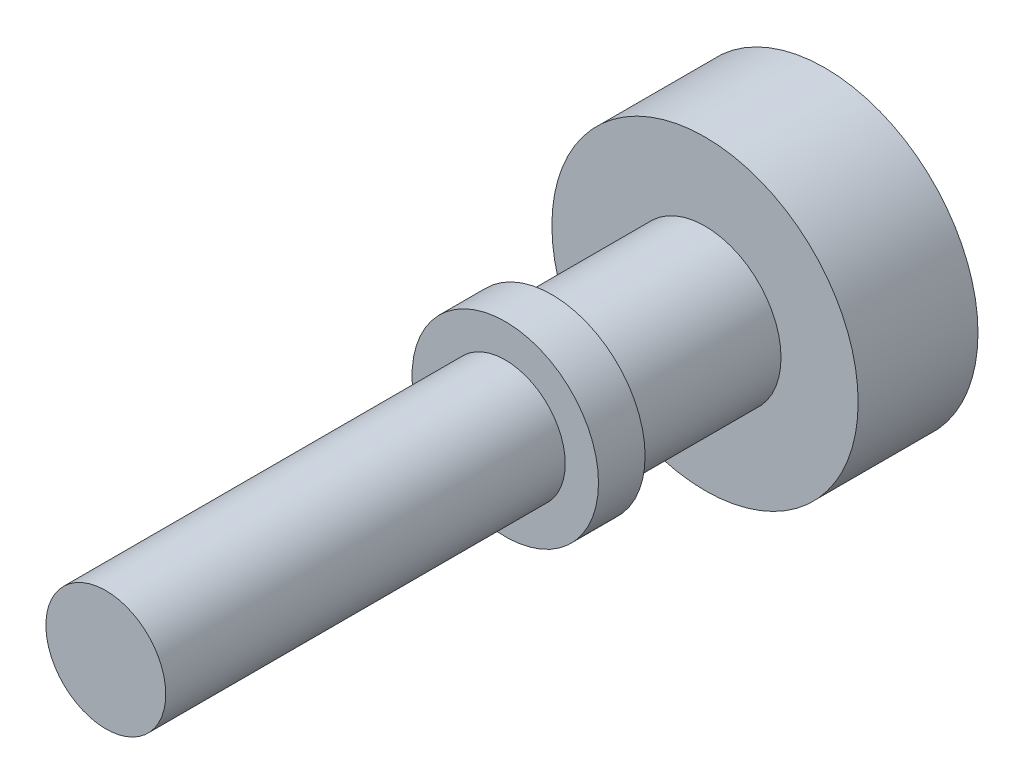
SolidWorks part; units mm, degrees
ref_plane "Front Plane" through (0, 0, 0) normal (0, 0, 1) x (1, 0, 0)
ref_plane "Top Plane" through (0, 0, 0) normal (0, 1, 0) x (1, 0, 0)
ref_plane "Right Plane" through (0, 0, 0) normal (1, 0, 0) x (0, 0, -1)
sketch "Sketch1" plane through (0, 0, 0) normal (0, 0, 1) x (1, 0, 0)
  circle A0 centre (0, 0) radius 5.75
  dimension "D1" = 11.5
extrude "Boss-Extrude1" add sketch "Sketch1" along normal blind 4.5 contours A0
sketch "Sketch2" plane through (0, 0, 4.5) normal (0, 0, 1) x (1, 0, 0)
  circle A0 centre (0, 0) radius 2.8536
extrude "Boss-Extrude2" add sketch "Sketch2" along normal blind 5.75
sketch "Sketch3" plane through (0, 0, 10.25) normal (0, 0, 1) x (1, 0, 0)
  circle A0 centre (0, 0) radius 3.5
  dimension "D1" = 7
extrude "Boss-Extrude3" add sketch "Sketch3" along normal blind 1.75
sketch "Sketch4" plane through (0, 0, 12) normal (0, 0, 1) x (1, 0, 0)
  circle A0 centre (0, 0) radius 2.25
  dimension "D1" = 4.5
extrude "Boss-Extrude4" add sketch "Sketch4" along normal blind 15
